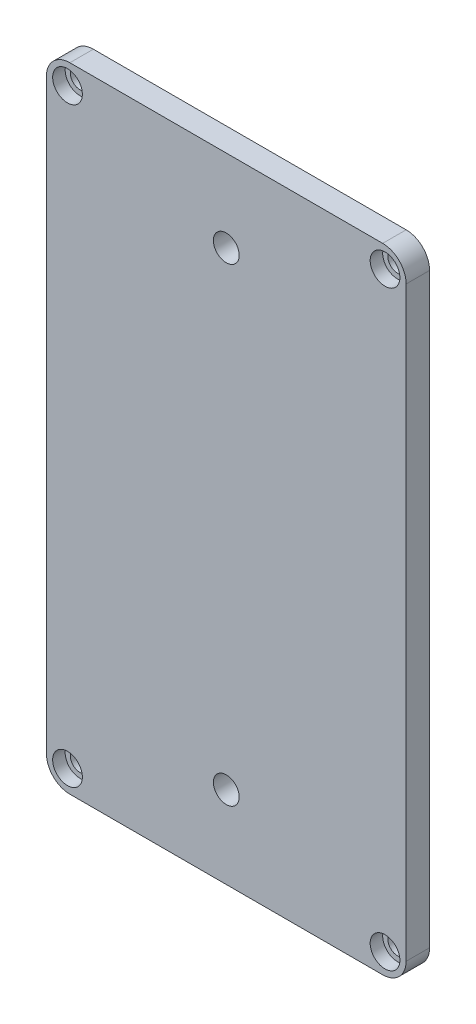
SolidWorks part; units mm, degrees
ref_plane "Front Plane" through (0, 0, 0) normal (0, 0, 1) x (1, 0, 0)
ref_plane "Top Plane" through (0, 0, 0) normal (0, 1, 0) x (1, 0, 0)
ref_plane "Right Plane" through (0, 0, 0) normal (1, 0, 0) x (0, 0, -1)
sketch "Sketch1" plane through (0, 0, 0) normal (0, 0, 1) x (1, 0, 0)
  line L0 (0, 40.5) -> (0, 0) construction
  line L1 (-23, -40.5) -> (23, -40.5)
  line L2 (-23, -40.5) -> (-23, 40.5)
  line L3 (-23, 40.5) -> (23, 40.5)
  line L4 (23, -40.5) -> (23, 40.5)
  line L5 (0, 0) -> (23, 0) construction
  circle A0 centre (-20.3, 37.8) radius 1.25
  circle A1 centre (20.3, 37.8) radius 1.25
  circle A2 centre (20.3, -37.8) radius 1.25
  circle A3 centre (-20.3, -37.8) radius 1.25
  point P0 (0, 0)
  dimension "D3" = 2.5
  dimension "D1" = 46
  dimension "D2" = 81
  dimension "D4" = 2.7
  dimension "D5" = 2.7
extrude "Boss-Extrude1" add sketch "Sketch1" along normal blind 3
fillet "Fillet1" radius 3 4 edges at (23, -40.5, 1.5) (-23, -40.5, 1.5) (23, 40.5, 1.5) (-23, 40.5, 1.5)
sketch "Sketch4" plane through (0, 0, 3) normal (0, 0, 1) x (1, 0, 0)
  line L0 (0, 40.5) -> (0, 0) construction
  line L1 (20, 40.5) -> (-20, 40.5) construction
  line L2 (0, 0) -> (23, 0) construction
  line L3 (23, -37.5) -> (23, 37.5) construction
  circle A0 centre (20.3, 37.8) radius 1.9
  circle A1 centre (-20.3, 37.8) radius 1.9
  circle A2 centre (-20.3, -37.8) radius 1.9
  circle A3 centre (20.3, -37.8) radius 1.9
  dimension "D1" = 3.8
extrude "Cut-Extrude2" cut sketch "Sketch4" against normal blind 1.6
sketch "Sketch5" plane through (0, 0, 3) normal (0, 0, 1) x (1, 0, 0)
  line L0 (0, 0) -> (0, 30) construction
  line L1 (0, 0) -> (-23, 0) construction
  line L2 (-23, 37.5) -> (-23, -37.5) construction
  circle A0 centre (0, 30) radius 1.65
  circle A1 centre (0, -30) radius 1.65
  dimension "D2" = 3.3
  dimension "D1" = 30
extrude "Cut-Extrude3" cut sketch "Sketch5" against normal blind 10
